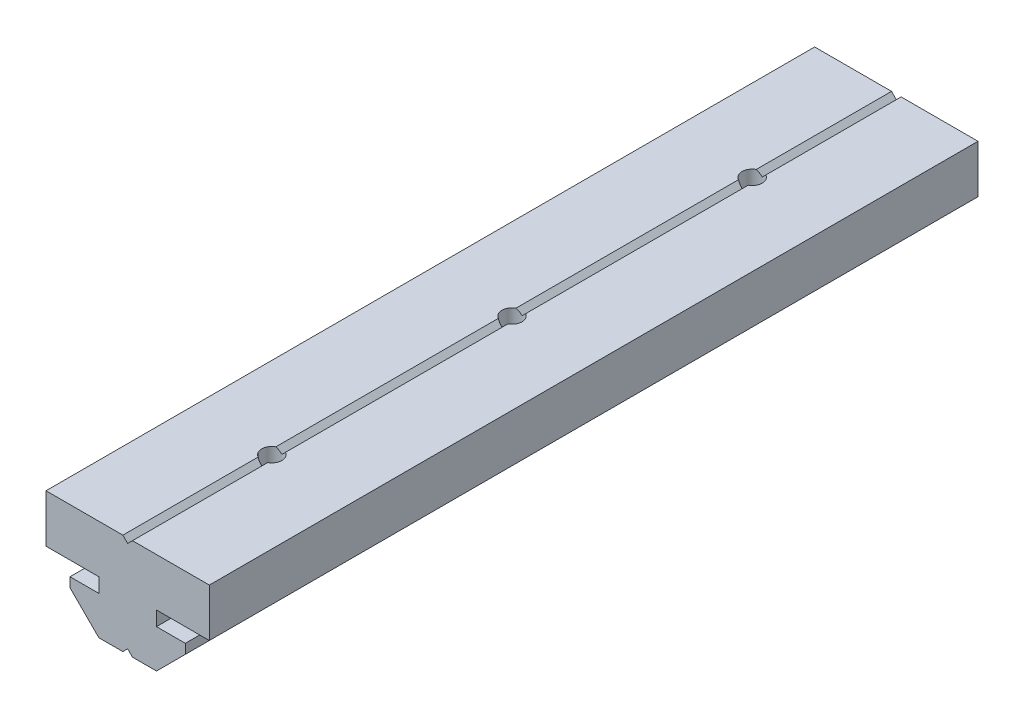
SolidWorks part; units mm, degrees
ref_plane "Plan de face" through (0, 0, 0) normal (0, 0, 1) x (1, 0, 0)
ref_plane "Plan de dessus" through (0, 0, 0) normal (0, 1, 0) x (1, 0, 0)
ref_plane "Plan de droite" through (0, 0, 0) normal (1, 0, 0) x (0, 0, -1)
sketch "Esquisse1" plane through (0, 0, 0) normal (0, 0, 1) x (1, 0, 0)
  line L0 (0, 0) -> (0, 10) construction
  line L1 (0, 10) -> (0.5, 10.5)
  line L2 (0.5, 10.5) -> (8.5, 10.5)
  line L3 (8.5, 10.5) -> (8.5, 5.5)
  line L4 (8.5, 5.5) -> (3, 5.5)
  line L5 (3, 5.5) -> (3, 4)
  line L6 (3, 4) -> (6, 4)
  line L7 (6, 4) -> (6, 3)
  line L8 (6, 3) -> (3, 0)
  line L9 (3, 0) -> (0.5, 0)
  line L10 (0.5, 0) -> (0, 0.5)
  line L11 (-0.5, 0) -> (0, 0.5)
  line L12 (-3, 0) -> (-0.5, 0)
  line L13 (-6, 3) -> (-3, 0)
  line L14 (-6, 4) -> (-6, 3)
  line L15 (-3, 4) -> (-6, 4)
  line L16 (-3, 5.5) -> (-3, 4)
  line L17 (-8.5, 5.5) -> (-3, 5.5)
  line L18 (-8.5, 10.5) -> (-8.5, 5.5)
  line L19 (-0.5, 10.5) -> (-8.5, 10.5)
  line L20 (0, 10) -> (-0.5, 10.5)
  dimension "D1" = 5
  dimension "D2" = 17
  dimension "D3" = 0.5
  dimension "D4" = 0.5
  dimension "D5" = 1.5
  dimension "D6" = 3
  dimension "D7" = 4
  dimension "D8" = 12
  dimension "D9" = 6
  dimension "D10" = 135
extrude "Boss.-Extru.1" add sketch "Esquisse1" along normal blind 80
sketch "Esquisse2" plane through (0, 10.5, 0) normal (0, 1, 0) x (1, 0, 0)
  line L0 (0, 0) -> (0, -80) construction
  line L1 (0, -80) -> (0, 0) construction
  line L2 (-0.5, -80) -> (-8.5, -80) construction
  circle A0 centre (0, -65) radius 1.05
  circle A1 centre (0, -40) radius 1.05
  circle A2 centre (0, -15) radius 1.05
  dimension "D1" = 2.1
  dimension "D2" = 25
  dimension "D3" = 25
  dimension "D4" = 15
extrude "Enlèv. mat.-Extru.1" cut sketch "Esquisse2" against normal through all
